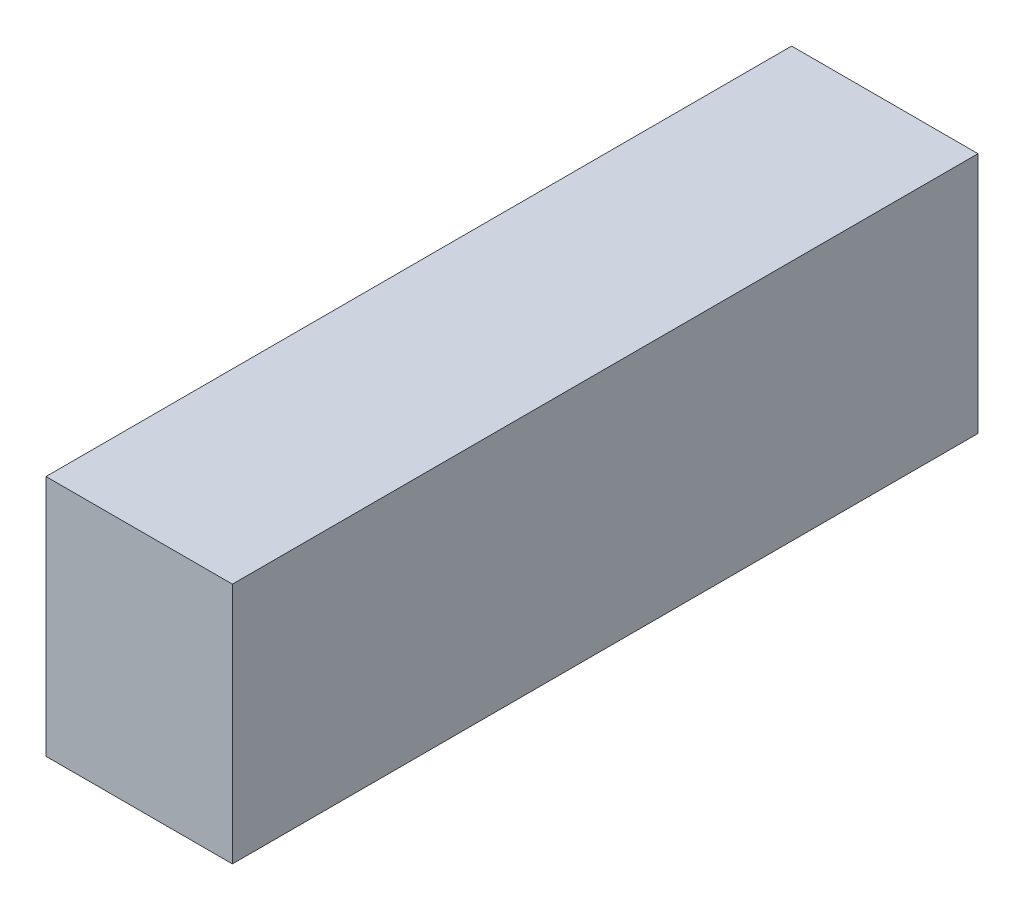
SolidWorks part; units mm, degrees
ref_plane "Front Plane" through (0, 0, 0) normal (0, 0, 1) x (1, 0, 0)
ref_plane "Top Plane" through (0, 0, 0) normal (0, 1, 0) x (1, 0, 0)
ref_plane "Right Plane" through (0, 0, 0) normal (1, 0, 0) x (0, 0, -1)
sketch "Sketch1" plane through (0, 0, 0) normal (1, 0, 0) x (0, 0, -1)
  line L1 (0, 0) -> (40, 0)
  line L2 (0, 0) -> (0, 13)
  line L3 (0, 13) -> (40, 13)
  line L4 (40, 0) -> (40, 13)
extrude "Boss-Extrude1" add sketch "Sketch1" along normal blind 10
